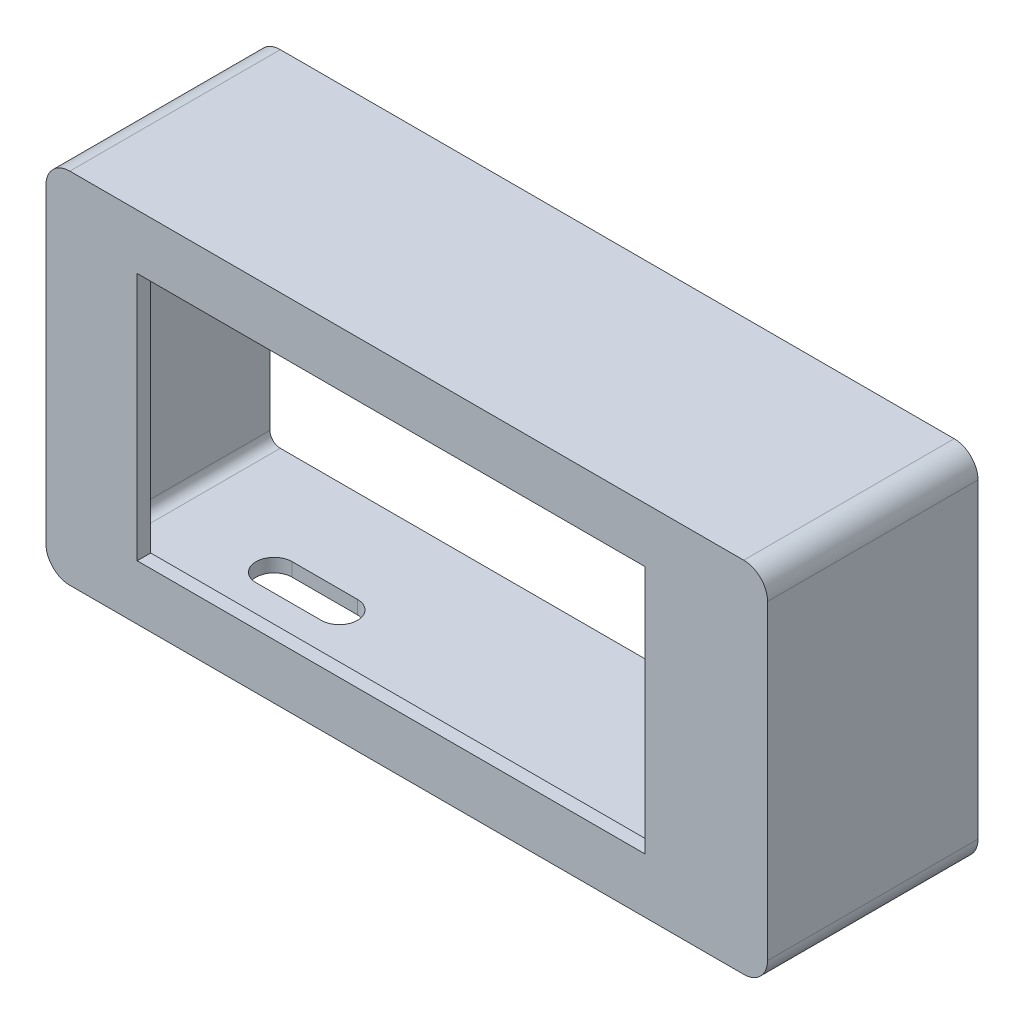
SolidWorks part; units mm, degrees
ref_plane "前视基准面" through (0, 0, 0) normal (0, 0, 1) x (1, 0, 0)
ref_plane "上视基准面" through (0, 0, 0) normal (0, 1, 0) x (1, 0, 0)
ref_plane "右视基准面" through (0, 0, 0) normal (1, 0, 0) x (0, 0, -1)
sketch "草图1" plane through (0, 0, 0) normal (1, 0, 0) x (0, 0, -1)
  line L1 (-9.5, -16) -> (9.5, -16)
  line L2 (-9.5, -16) -> (-9.5, 16)
  line L3 (-9.5, 16) -> (9.5, 16)
  line L4 (9.5, -16) -> (9.5, 16)
  line L5 (-9.5, -16) -> (9.5, 16) construction
  line L6 (-9.5, 16) -> (9.5, -16) construction
  point P0 (0, 0)
  dimension "D1" = 19
  dimension "D2" = 32
extrude "凸台-拉伸1" add sketch "草图1" along normal blind 67
fillet "圆角1" radius 1 4 edges at (67, -16, 0) (0, -16, 0) (0, 16, 0) (67, 16, 0)
shell "抽壳1" thickness 1.3
ref_plane "基准面4" through (0, 0, 3) normal (0, 0, -1) x (-1, 0, 0)
sketch "草图2" plane through (0, 0, 10.8) normal (0, 0, 1) x (1, 0, 0)
  line L1 (7.5, 12) -> (56.5, 12)
  line L2 (7.5, 12) -> (7.5, -12)
  line L3 (7.5, -12) -> (56.5, -12)
  line L4 (56.5, 12) -> (56.5, -12)
  line L5 (68.3, 15) -> (68.3, -15) construction
  line L6 (67, 15) -> (67, -15) construction
  point P8 (56.5, 0)
  point P11 (68.3, 0)
  dimension "D1" = 49
  dimension "D2" = 24
  dimension "D3" = 10.5
extrude "切除-拉伸1" cut sketch "草图2" against normal through all
sketch "草图3" plane through (0, -17.3, 0) normal (0, -1, 0) x (1, 0, 0)
  line L0 (11.05, 1.15) -> (17.35, 1.15) construction
  line L1 (11.05, 2.9) -> (17.35, 2.9)
  line L2 (11.05, -0.6) -> (17.35, -0.6)
  line L3 (0, 9.5) -> (0, -9.5) construction
  line L4 (-24.7848, 3) -> (24.7848, 3) construction
  arc A0 (11.05, 2.9) -> (11.05, -0.6) centre (11.05, 1.15) ccw
  arc A1 (17.35, -0.6) -> (17.35, 2.9) centre (17.35, 1.15) ccw
  point P2 (14.2, 1.15)
  point P7 (9.3, 1.15)
  point P8 (19.1, 1.15)
  dimension "D1" = 9.8
  dimension "D2" = 3.5
  dimension "D3" = 9.3
  dimension "D4" = 0.1
extrude "切除-拉伸2" cut sketch "草图3" against normal up to next
sketch "草图4" plane through (0, 16, 0) normal (0, -1, 0) x (1, 0, 0)
  line L0 (-24.7848, 3) -> (24.7848, 3) construction
  line L1 (7.4307, 3) -> (13.2168, 3)
  line L2 (7.4307, 3) -> (7.4307, 1)
  line L3 (7.4307, 1) -> (13.2168, 1)
  line L4 (13.2168, 3) -> (13.2168, 1)
  line L6 (55.2382, 1) -> (61.0473, 1)
  line L7 (55.2382, 1) -> (55.2382, 3)
  line L8 (55.2382, 3) -> (61.0473, 3)
  line L9 (61.0473, 1) -> (61.0473, 3)
  dimension "D1" = 2
extrude "凸台-拉伸2" add sketch "草图4" along normal blind 1.3
